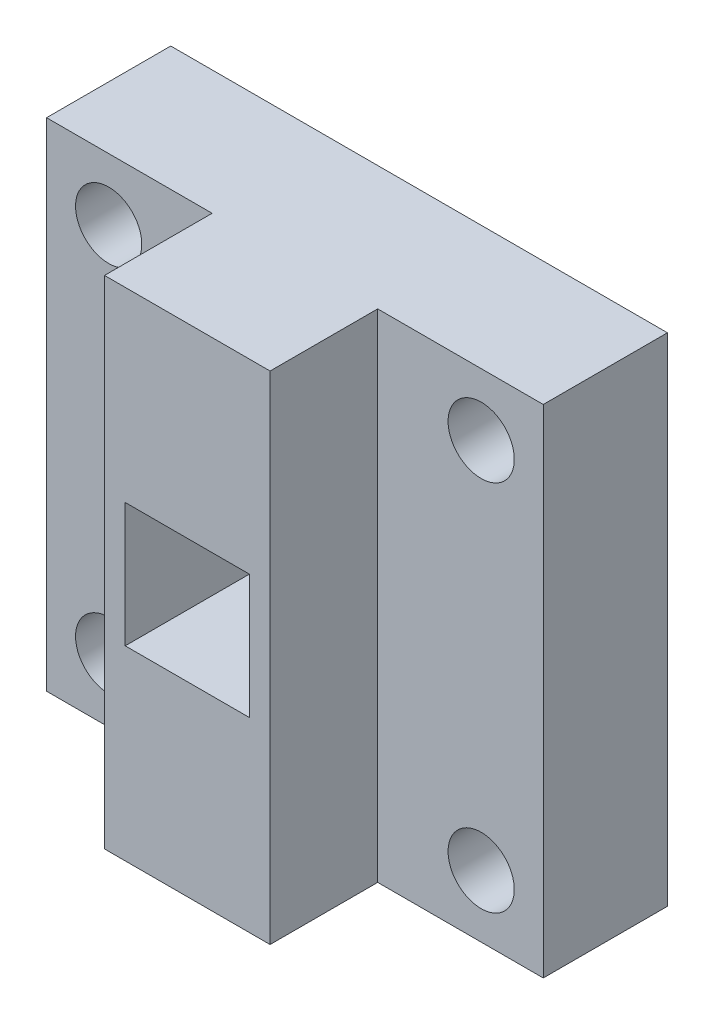
SolidWorks part; units mm, degrees
ref_plane "Спереди" through (0, 0, 0) normal (0, 0, 1) x (1, 0, 0)
ref_plane "Сверху" through (0, 0, 0) normal (0, 1, 0) x (1, 0, 0)
ref_plane "Справа" through (0, 0, 0) normal (1, 0, 0) x (0, 0, -1)
sketch "Эскиз1" plane through (0, 0, 0) normal (0, 0, 1) x (1, 0, 0)
  line L1 (-30, -30) -> (30, -30)
  line L2 (-30, -30) -> (-30, 30)
  line L3 (-30, 30) -> (30, 30)
  line L4 (30, -30) -> (30, 30)
  line L5 (-30, -30) -> (30, 30) construction
  line L6 (-30, 30) -> (30, -30) construction
  point P0 (0, 0)
  dimension "D1" = 60
extrude "Бобышка-Вытянуть1" add sketch "Эскиз1" along normal blind 15
sketch "Эскиз2" plane through (0, 0, 15) normal (0, 0, 1) x (1, 0, 0)
  line L0 (30, 30) -> (-30, 30) construction
  line L1 (-10, -30) -> (10, -30)
  line L2 (-10, -30) -> (-10, 30)
  line L3 (-10, 30) -> (10, 30)
  line L4 (10, -30) -> (10, 30)
  line L5 (-10, -30) -> (10, 30) construction
  line L6 (-10, 30) -> (10, -30) construction
  point P0 (0, 0)
  dimension "D1" = 20
extrude "Бобышка-Вытянуть2" add sketch "Эскиз2" along normal blind 13
sketch "Эскиз3" plane through (0, 0, 28) normal (0, 0, 1) x (1, 0, 0)
  line L1 (-7.5, -7.5) -> (7.5, -7.5)
  line L2 (-7.5, -7.5) -> (-7.5, 7.5)
  line L3 (-7.5, 7.5) -> (7.5, 7.5)
  line L4 (7.5, -7.5) -> (7.5, 7.5)
  line L5 (-7.5, -7.5) -> (7.5, 7.5) construction
  line L6 (-7.5, 7.5) -> (7.5, -7.5) construction
  point P0 (0, 0)
  dimension "D1" = 15
extrude "Вырез-Вытянуть1" cut sketch "Эскиз3" against normal through all
sketch "Эскиз5" plane through (0, 0, 0) normal (0, 0, -1) x (-1, 0, 0)
  line L0 (30, -30) -> (-30, -30) construction
  line L1 (-30, -30) -> (-30, 30) construction
  circle A0 centre (-22.5, -22.5) radius 4
  dimension "D1" = 8
  dimension "D2" = 7.5
  dimension "D3" = 7.5
extrude "Вырез-Вытянуть3" cut sketch "Эскиз5" against normal through all
mirror "Зеркальное отражение1" about plane through (0, 0, 0) normal (0, 1, 0) of "Вырез-Вытянуть3"
mirror "Зеркальное отражение2" about plane through (0, 0, 0) normal (1, 0, 0) of "Зеркальное отражение1", "Вырез-Вытянуть3"
